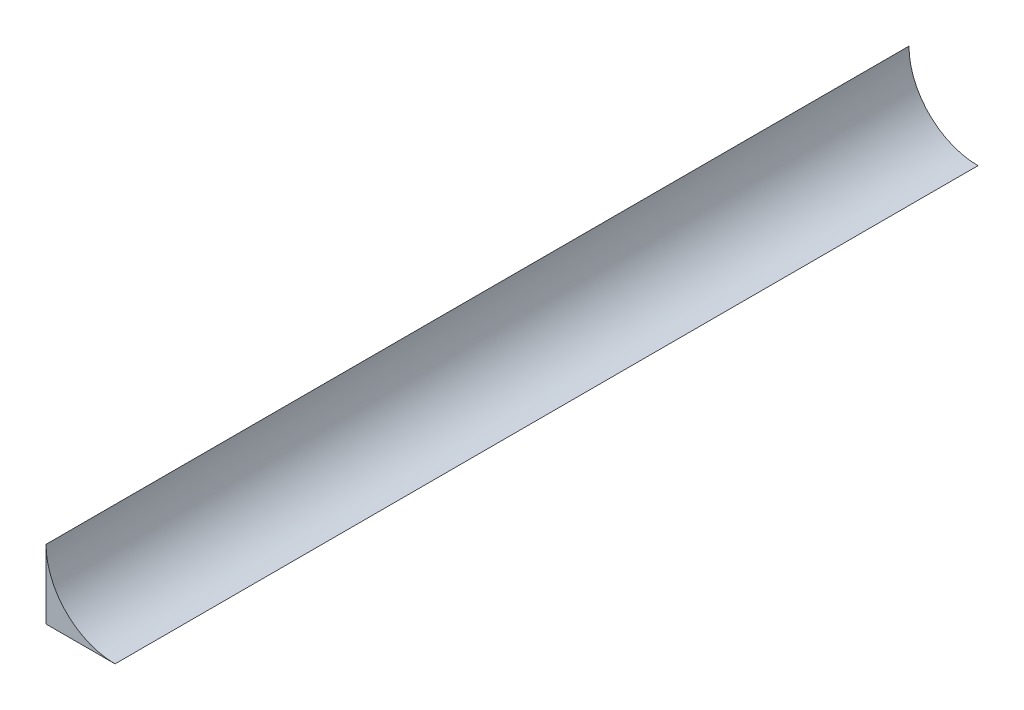
SolidWorks part; units mm, degrees
material "MDF"
ref_plane "Front Plane" through (0, 0, 0) normal (0, 0, 1) x (1, 0, 0)
ref_plane "Top Plane" through (0, 0, 0) normal (0, 1, 0) x (1, 0, 0)
ref_plane "Right Plane" through (0, 0, 0) normal (1, 0, 0) x (0, 0, -1)
sketch "Sketch1" plane through (0, 0, 0) normal (0, 0, 1) x (1, 0, 0)
  line L0 (0, 12.7) -> (0, 0)
  line L1 (0, -55) -> (0, 55) construction
  line L2 (0, 0) -> (12.7, 0)
  line L3 (55, 0) -> (-55, 0) construction
  arc A0 (12.7, 0) -> (0, 12.7) centre (12.7, 12.7) cw
  dimension "D1" = 12.7
extrude "Boss-Extrude1" add sketch "Sketch1" along normal mid plane 158.75
